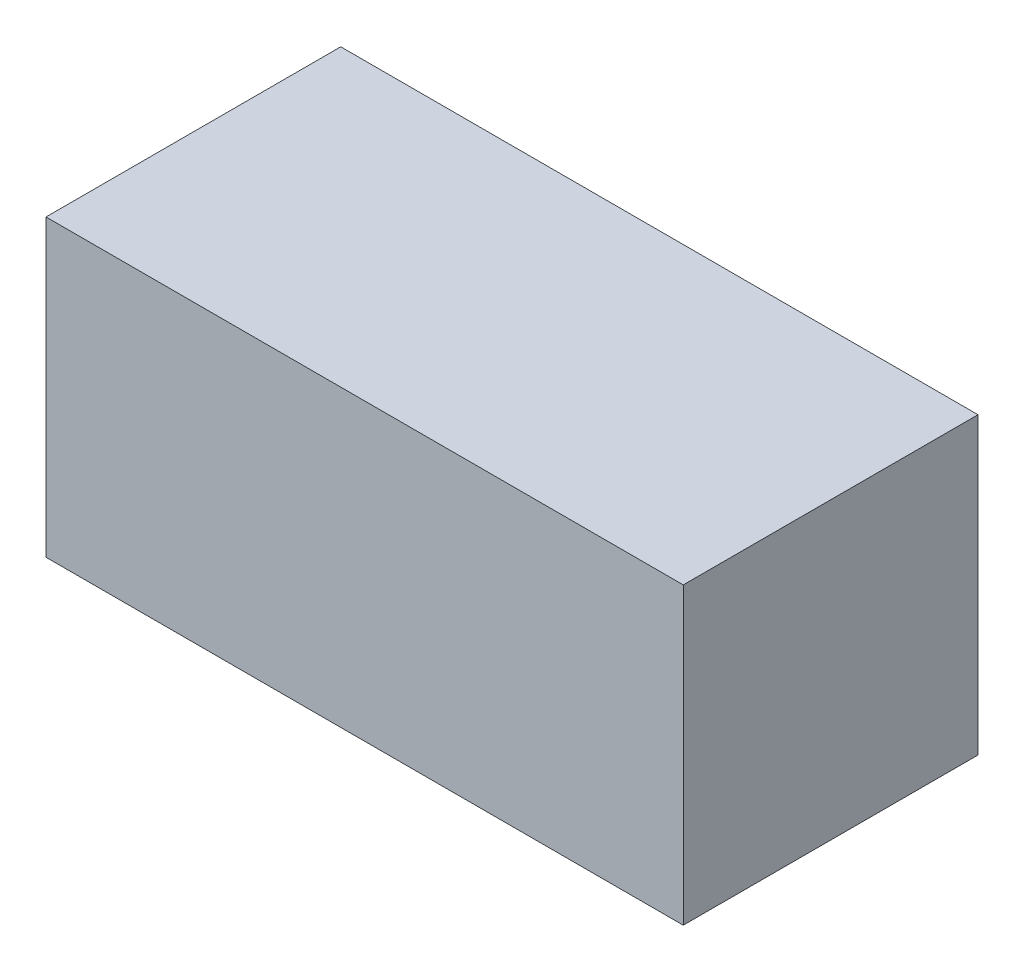
SolidWorks part; units mm, degrees
ref_plane "Front Plane" through (0, 0, 0) normal (0, 0, 1) x (1, 0, 0)
ref_plane "Top Plane" through (0, 0, 0) normal (0, 1, 0) x (1, 0, 0)
ref_plane "Right Plane" through (0, 0, 0) normal (1, 0, 0) x (0, 0, -1)
other "Configuration Table"
sketch "Sketch1" plane through (0, 0, 0) normal (0, 0, 1) x (1, 0, 0)
  line L1 (48, -18.5) -> (128, -18.5)
  line L2 (48, -18.5) -> (48, 18.5)
  line L3 (48, 18.5) -> (128, 18.5)
  line L4 (128, -18.5) -> (128, 18.5)
extrude "MTG_motor_24V_37x37x80_1" add sketch "Sketch1" against normal blind 37 from offset 18.5 separate body
